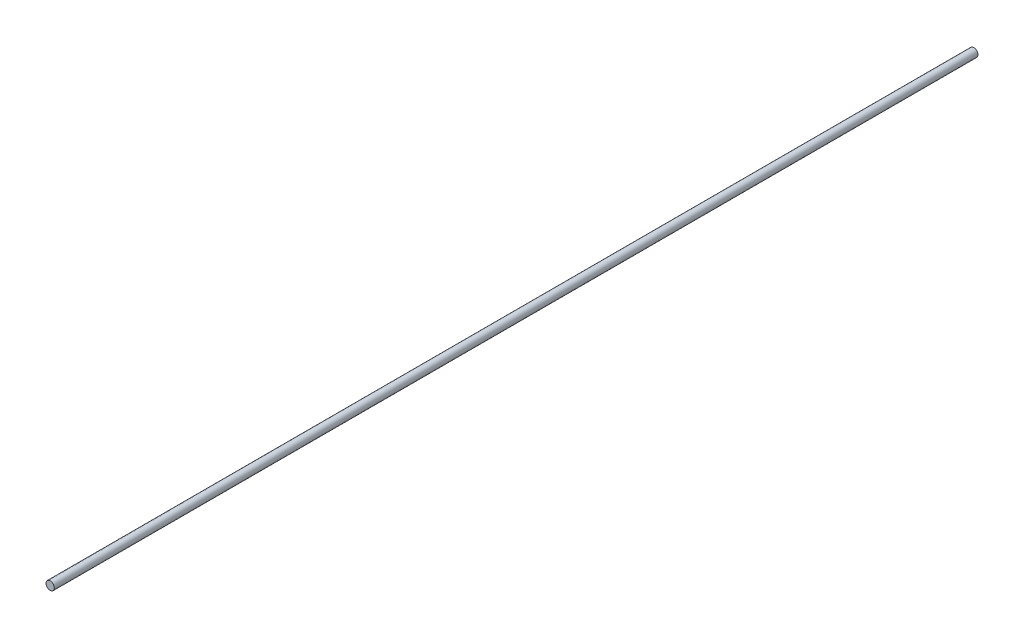
SolidWorks part; units mm, degrees
ref_plane "Front Plane" through (0, 0, 0) normal (0, 0, 1) x (1, 0, 0)
ref_plane "Top Plane" through (0, 0, 0) normal (0, 1, 0) x (1, 0, 0)
ref_plane "Right Plane" through (0, 0, 0) normal (1, 0, 0) x (0, 0, -1)
sketch "Sketch1" plane through (0, 0, 0) normal (0, 0, 1) x (1, 0, 0)
  circle A0 centre (0, 0) radius 9
  dimension "D1" = 18
extrude "Boss-Extrude1" add sketch "Sketch1" along normal mid plane 2000
